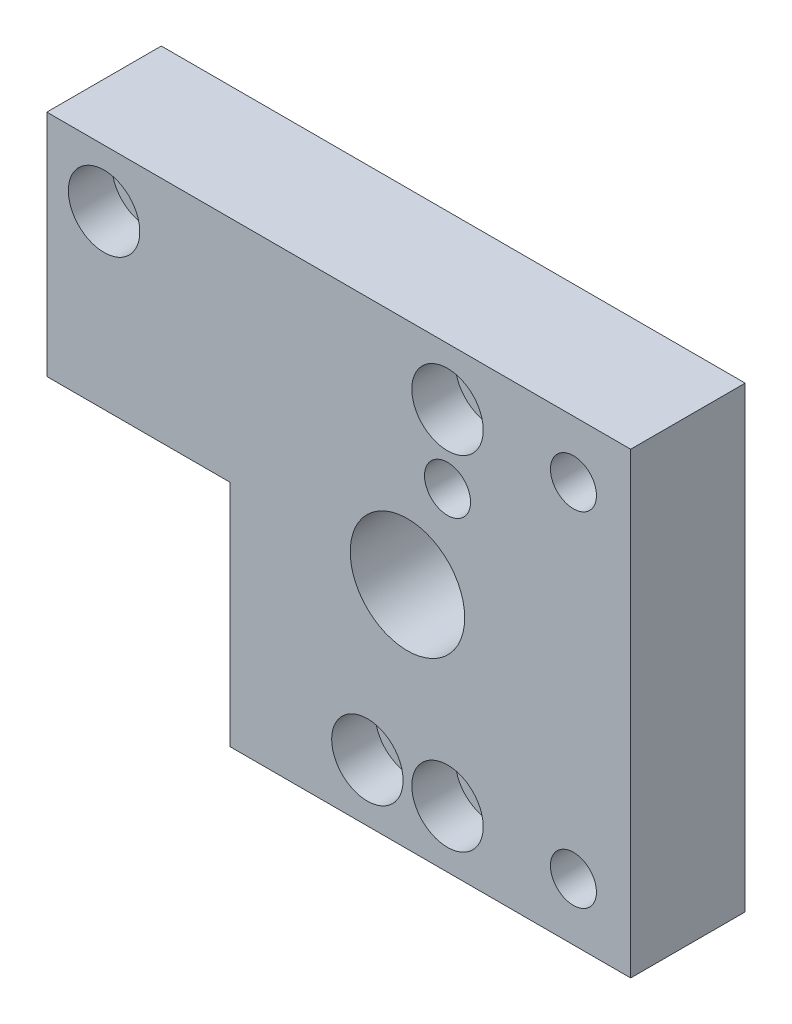
SolidWorks part; units mm, degrees
material "1060 Alloy"
ref_plane "Front Plane" through (0, 0, 0) normal (0, 0, 1) x (1, 0, 0)
ref_plane "Top Plane" through (0, 0, 0) normal (0, 1, 0) x (1, 0, 0)
ref_plane "Right Plane" through (0, 0, 0) normal (1, 0, 0) x (0, 0, -1)
sketch "Sketch1" plane through (0, 0, 0) normal (0, 0, 1) x (1, 0, 0)
  line L0 (0, 25.4) -> (0, 0) construction
  line L1 (-25.4, -25.4) -> (39.37, -25.4)
  line L2 (-25.4, -25.4) -> (-25.4, 25.4)
  line L3 (-25.4, 25.4) -> (39.37, 25.4)
  line L4 (39.37, -25.4) -> (39.37, 25.4)
  line L7 (39.37, 0) -> (-25.4, 0) construction
  circle A0 centre (-19.05, 19.05) radius 2.5527
  circle A1 centre (19.05, 19.05) radius 2.5527
  circle A2 centre (19.05, -19.05) radius 2.5527
  circle A3 centre (10.16, -19.05) radius 2.5527
  circle A4 centre (14.605, 0) radius 6.35
  point P0 (0, 0)
  dimension "D3" = 5.1054
  dimension "D7" = 12.7
  dimension "D1" = 64.77
  dimension "D2" = 50.8
  dimension "D4" = 38.1
  dimension "D5" = 6.35
  dimension "D6" = 4.445
  dimension "D8" = 38.1
  dimension "D9" = 8.89
  dimension "D10" = 25.4
extrude "Boss-Extrude1" add sketch "Sketch1" along normal blind 12.7
hole_wizard "#7 (0.201) Diameter Hole1" positions "Sketch4" profile "Sketch5" hole size "#7" standard "ANSI Inch"
sketch "Sketch4" plane through (-24.7212, -12.8643, 0) normal (0, 0, 1) x (1, 0, 0)
  line L0 (64.0912, -12.5357) -> (64.0912, 38.2643) construction
  line L2 (64.0912, 38.2643) -> (-0.6788, 38.2643) construction
  circle A5 centre (43.7712, -6.1857) radius 2.5527 construction
  circle A6 centre (43.7712, -6.1857) radius 2.5527 construction
  circle A7 centre (43.7712, 31.9143) radius 2.5527 construction
  point P0 (57.7412, -6.1857)
  point P7 (57.7412, 31.9143)
  point P33 (43.7712, 24.2943)
  dimension "D3" = 7.62
  dimension "D1" = 6.35
  dimension "D2" = 6.35
sketch "Sketch5" plane through (33.02, -19.05, 0) normal (1, 0, 0) x (0, 1, 0)
  line L0 (0, 0) -> (0, 71.6378)
  line L1 (0, 71.6378) -> (2.5527, 70.104)
  line L2 (2.5527, 70.104) -> (2.5527, 0)
  line L5 (2.5527, 0) -> (0, 0)
  line L10 (0, 71.6378) -> (-2.5527, 70.104) construction
  line L11 (0, -6.35) -> (0, 107.95) construction
  dimension "Hole Dia." = 5.1054
  dimension "Hole Depth" = 70.104
  dimension "Drill Angle" = 118
sketch "Sketch6" plane through (0, 0, 12.7) normal (0, 0, -1) x (-1, 0, 0)
  circle A0 centre (-19.05, 19.05) radius 3.9624
  circle A3 centre (-19.05, -19.05) radius 3.9624
  circle A4 centre (-10.16, -19.05) radius 3.9624
  circle A5 centre (19.05, 19.05) radius 3.9624
  dimension "D1" = 7.9248
extrude "Cut-Extrude1" cut sketch "Sketch6" along normal blind 4.826
sketch "Sketch7" plane through (0, 0, 0) normal (0, 0, -1) x (-1, 0, 0)
  line L1 (25.4, -25.4) -> (5.08, -25.4)
  line L2 (25.4, -25.4) -> (25.4, 0)
  line L3 (25.4, 0) -> (5.08, 0)
  line L4 (5.08, -25.4) -> (5.08, 0)
  dimension "D1" = 20.32
extrude "Cut-Extrude2" cut sketch "Sketch7" against normal through all
